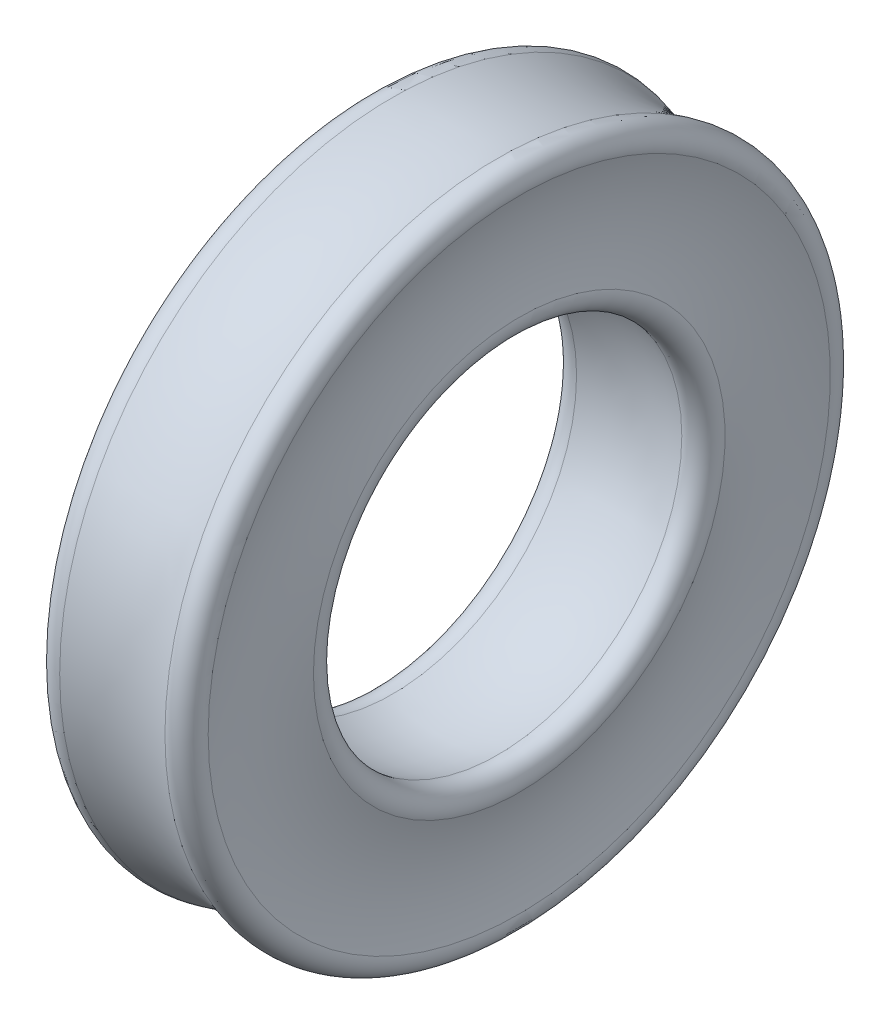
SolidWorks part; units mm, degrees
material "橡胶"
ref_plane "前视基准面" through (0, 0, 0) normal (0, 0, 1) x (1, 0, 0)
ref_plane "上视基准面" through (0, 0, 0) normal (0, 1, 0) x (1, 0, 0)
ref_plane "右视基准面" through (0, 0, 0) normal (1, 0, 0) x (0, 0, -1)
sketch "草图1" plane through (0, 0, 0) normal (0, 0, 1) x (1, 0, 0)
  line L0 (0, 0) -> (1.31, 0) construction
  line L1 (-0.9182, 5.8056) -> (0.9182, 5.8056) construction
  line L2 (-1.31, 5.82) -> (1.31, 5.82) construction
  line L3 (-1.31, 5.82) -> (-1.31, 3.2) construction
  line L4 (-1.31, 3.2) -> (1.31, 3.2) construction
  line L5 (1.31, 5.82) -> (1.31, 3.2) construction
  line L6 (-1.2956, 5.4282) -> (-1.2956, 3.5918) construction
  line L7 (-0.9182, 3.2144) -> (0.9182, 3.2144) construction
  line L8 (1.2956, 3.5918) -> (1.2956, 5.4282) construction
  line L9 (0, 0) -> (0, 3.2) construction
  arc A0 (-0.9182, 5.8056) -> (-1.2956, 5.4282) centre (-1.01, 5.52) ccw
  arc A1 (0.9182, 5.8056) -> (1.2956, 5.4282) centre (1.01, 5.52) cw
  arc A2 (-0.9182, 5.8056) -> (0.9182, 5.8056) centre (0, 8.6616) ccw
  arc A3 (-1.2956, 3.5918) -> (-0.9182, 3.2144) centre (-1.01, 3.5) ccw
  arc A4 (0.9182, 3.2144) -> (1.2956, 3.5918) centre (1.01, 3.5) ccw
  arc A5 (-1.2956, 5.4282) -> (-1.2956, 3.5918) centre (-4.1516, 4.51) cw
  arc A6 (1.2956, 5.4282) -> (1.2956, 3.5918) centre (4.1516, 4.51) ccw
  arc A7 (-0.9182, 3.2144) -> (0.9182, 3.2144) centre (0, 0.3584) cw
  dimension "D3" = 0.3
  dimension "D4" = 0.3
  dimension "D5" = 3
  dimension "D1" = 2.62
  dimension "D2" = 3.2
revolve "旋转1" add sketch "草图1" angle 360 about L0
sketch "草图2" plane through (0, 0, 0) normal (1, 0, 0) x (0, 0, -1)
  circle A0 centre (0, 0) radius 2.25
  dimension "D1" = 4.5
